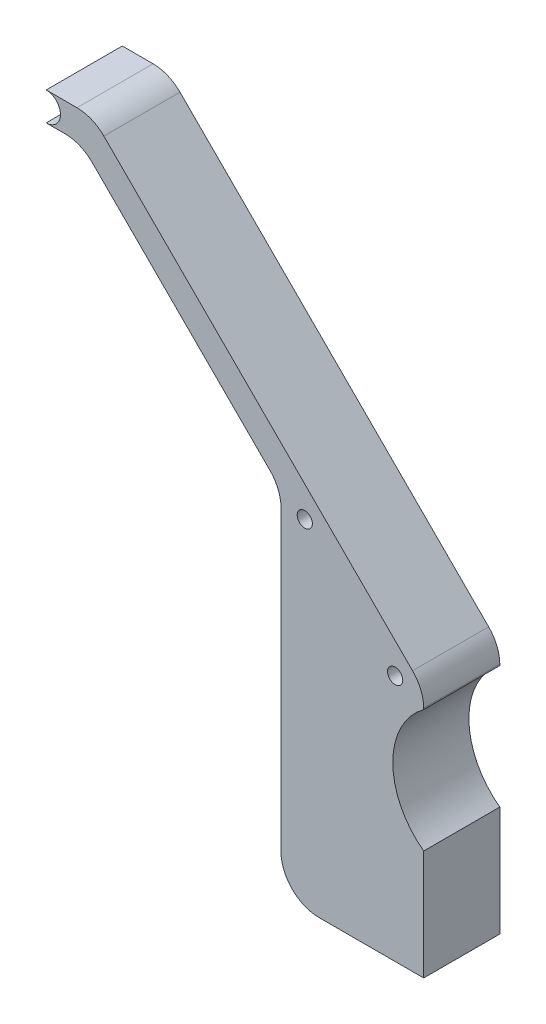
SolidWorks part; units mm, degrees
material "ABS"
ref_plane "Спереди" through (0, 0, 0) normal (0, 0, 1) x (1, 0, 0)
ref_plane "Сверху" through (0, 0, 0) normal (0, 1, 0) x (1, 0, 0)
ref_plane "Справа" through (0, 0, 0) normal (1, 0, 0) x (0, 0, -1)
sketch "Эскиз1" plane through (0, 0, 0) normal (0, 0, 1) x (1, 0, 0)
  line L0 (0.0303, 5) -> (-14.9697, 5)
  line L1 (-14.9697, 5) -> (-14.9697, 18.9697)
  line L2 (-14.9697, 18.9697) -> (-36, 40)
  line L4 (-34.7574, 43) -> (0.0303, 8.2123)
  line L6 (0.0303, 8.2123) -> (0.0303, 5)
  line L8 (0.0303, 0) -> (0.0303, 61.3431) construction
  line L9 (-39.6497, 43) -> (-45.0997, 43) construction
  line L11 (-36, 40) -> (-39.6497, 40)
  line L12 (-34.7574, 43) -> (-39.6497, 43)
  arc A0 (-39.6497, 43) -> (-39.6497, 40) centre (-39.6497, 41.5) cw
  arc A1 (-39.6497, 40) -> (-39.6497, 43) centre (-39.6497, 41.5) ccw construction
  dimension "D1" = 135
  dimension "D2" = 15
  dimension "D4" = 3
  dimension "D6" = 4.8923
  dimension "D7" = 35
extrude "База" add sketch "Эскиз1" against normal blind 8
hole_wizard "Крепление M2" positions "Эскиз2" profile "Эскиз3" tap size "M2" standard "DIN" end condition through all
sketch "Эскиз2" plane through (0, 0, 0) normal (0, 0, 1) x (1, 0, 0)
  line L1 (-14.9697, 5) -> (0.0303, 5) construction
  line L2 (0.0303, 5) -> (0.0303, 8.2123) construction
  point P0 (-2.9697, 8)
  point P12 (-12.4697, 17.5)
  dimension "D1" = 3
  dimension "D2" = 3
  dimension "D3" = 12.5
  dimension "D4" = 12.5
sketch "Эскиз3" plane through (-2.9697, 8, 0) normal (1, 0, 0) x (0, -1, 0)
  line L0 (0, 0) -> (0, 8)
  line L1 (0, 8) -> (0.8, 8)
  line L2 (0.8, 8) -> (0.8, 0)
  line L5 (0.8, 0) -> (0, 0)
  line L11 (0, -6.35) -> (0, 107.95) construction
  dimension "Диаметр проходного сверла" = 1.6
  dimension "Глубина проходного сверла" = 8
cosmetic thread "Отверстие резьбы1" parameters "D2"=2
cosmetic thread "Отверстие резьбы2" parameters "D2"=2
sketch "Эскиз5" plane through (0, 0, 0) normal (0, 0, 1) x (1, 0, 0)
  line L0 (0.0303, 5) -> (0.0303, 8.2123) construction
  line L1 (-14.9697, 5) -> (0.0303, 5)
  line L2 (-14.9697, 5) -> (-14.9697, -18)
  line L3 (-14.9697, -18) -> (0.0303, -18)
  line L4 (0.0303, 5) -> (0.0303, -18)
  dimension "D1" = 23
extrude "Продолжение низа" add sketch "Эскиз5" against normal up to surface (8 mm away) up to face at (-2.1697, 8, -8)
fillet "Скругление1" radius 4 5 edges at (-36, 40, -4) (-14.9697, 18.9697, -4) (-34.7574, 43, -4) (0.0303, 8.2123, -4) (-14.9697, -18, -4)
sketch "Эскиз6" plane through (0, 0, 0) normal (0, 0, 1) x (1, 0, 0)
  line L0 (0.0303, 6.4372) -> (0.0303, -6.4372)
  line L3 (0.0303, -18) -> (0.0303, 6.5555) construction
  arc A2 (0.0303, 6.4372) -> (0.0303, -6.4372) centre (4.7803, 0) ccw
  dimension "D2" = 4.75
  dimension "D1" = 8
extrude "Вырез-Вытянуть1" cut sketch "Эскиз6" against normal through all
